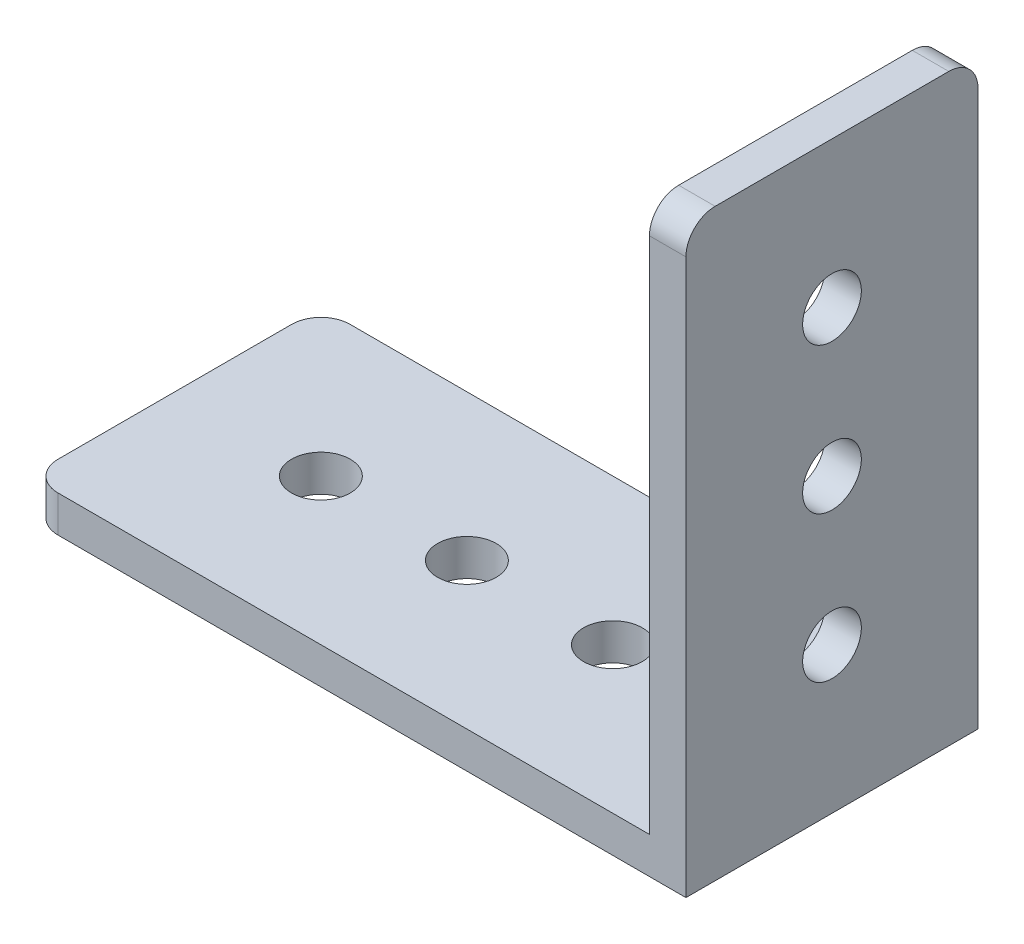
SolidWorks part; units mm, degrees
material "6061 Alloy"
ref_plane "Front" through (0, 0, 0) normal (0, 0, 1) x (1, 0, 0)
ref_plane "Top" through (0, 0, 0) normal (0, 1, 0) x (1, 0, 0)
ref_plane "Right" through (0, 0, 0) normal (1, 0, 0) x (0, 0, -1)
sketch "Sketch1" plane through (0, 0, 0) normal (0, 0, 1) x (1, 0, 0)
  line L0 (0, 0) -> (0, 50.8)
  line L1 (0, 50.8) -> (-3.175, 50.8)
  line L2 (-3.175, 50.8) -> (-3.175, 3.175)
  line L3 (-3.175, 3.175) -> (-57.15, 3.175)
  line L4 (-57.15, 3.175) -> (-57.15, 0)
  line L5 (-57.15, 0) -> (0, 0)
  dimension "D1" = 50.8
  dimension "D2" = 57.15
  dimension "D3" = 3.175
  dimension "D4" = 3.175
extrude "Boss-Extrude1" add sketch "Sketch1" along normal blind 25.4
fillet "Fillet1" radius 2.54 4 edges at (-57.15, 1.5875, 0) (-57.15, 1.5875, 25.4) (-1.5875, 50.8, 0) (-1.5875, 50.8, 25.4)
hole_wizard "#10 Clearance Hole1" positions "Sketch2" profile "Sketch3" hole size "#10" standard "ANSI Inch"
sketch "Sketch2" plane through (-3.175, 0, 0) normal (-1, 0, 0) x (0, 0, 1)
  line L1 (25.4, 3.175) -> (0, 3.175) construction
  line L2 (25.4, 48.26) -> (25.4, 3.175) construction
  point P0 (12.7, 38.1)
  point P2 (12.7, 25.4)
  point P4 (12.7, 12.7)
  dimension "D1" = 12.7
  dimension "D2" = 12.7
  dimension "D3" = 9.525
  dimension "D4" = 12.7
sketch "Sketch3" plane through (-3.175, 38.1, 12.7) normal (0, 1, 0) x (0, 0, 1)
  line L0 (0, 0) -> (0, 4.7078)
  line L1 (0, 4.7078) -> (2.5527, 3.174)
  line L2 (2.5527, 3.174) -> (2.5527, 0)
  line L5 (2.5527, 0) -> (0, 0)
  line L10 (0, 4.7078) -> (-2.5527, 3.174) construction
  line L11 (0, -6.35) -> (0, 107.95) construction
  dimension "Hole Dia." = 5.1054
  dimension "Hole Depth" = 3.174
  dimension "Drill Angle" = 118
hole_wizard "#10 Clearance Hole2" positions "Sketch4" profile "Sketch5" hole size "#10" standard "ANSI Inch"
sketch "Sketch4" plane through (0, 3.175, 0) normal (0, 1, 0) x (1, 0, 0)
  line L0 (-3.175, -25.4) -> (-3.175, 0) construction
  line L1 (-3.175, -25.4) -> (-54.61, -25.4) construction
  point P0 (-19.05, -12.7)
  point P2 (-31.75, -12.7)
  point P4 (-44.45, -12.7)
  dimension "D1" = 12.7
  dimension "D2" = 12.7
  dimension "D3" = 15.875
  dimension "D4" = 12.7
sketch "Sketch5" plane through (-19.05, 3.175, 12.7) normal (1, 0, 0) x (0, 0, 1)
  line L0 (0, 0) -> (0, 4.7078)
  line L1 (0, 4.7078) -> (2.5527, 3.174)
  line L2 (2.5527, 3.174) -> (2.5527, 0)
  line L5 (2.5527, 0) -> (0, 0)
  line L10 (0, 4.7078) -> (-2.5527, 3.174) construction
  line L11 (0, -6.35) -> (0, 107.95) construction
  dimension "Hole Dia." = 5.1054
  dimension "Hole Depth" = 3.174
  dimension "Drill Angle" = 118
